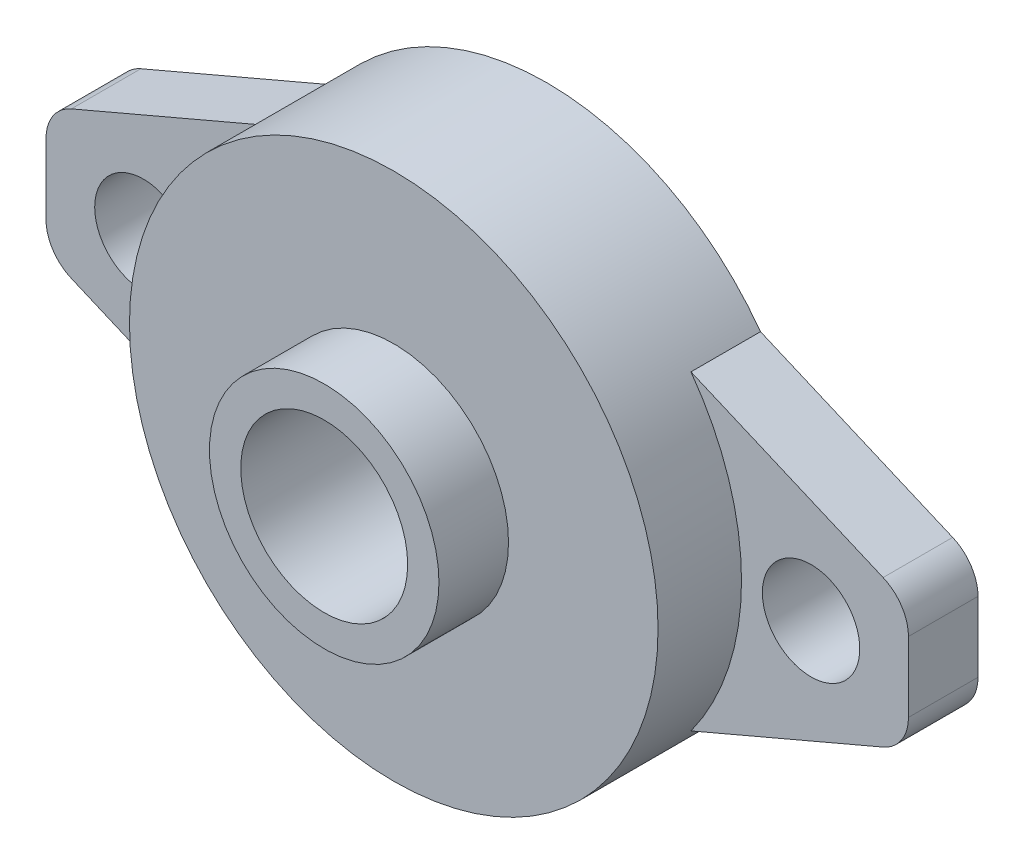
SolidWorks part; units mm, degrees
ref_plane "Front Plane" through (0, 0, 0) normal (0, 0, 1) x (1, 0, 0)
ref_plane "Top Plane" through (0, 0, 0) normal (0, 1, 0) x (1, 0, 0)
ref_plane "Right Plane" through (0, 0, 0) normal (1, 0, 0) x (0, 0, -1)
sketch "Sketch1" plane through (0, 0, 0) normal (0, 0, 1) x (1, 0, 0)
  circle A0 centre (0, 0) radius 19
  circle A1 centre (0, 0) radius 6
  dimension "D1" = 38
  dimension "D2" = 12
extrude "Boss-Extrude1" add sketch "Sketch1" along normal blind 11
sketch "Sketch2" plane through (0, 0, 11) normal (0, 0, 1) x (1, 0, 0)
  circle A0 centre (0, 0) radius 8.25
  circle A1 centre (0, 0) radius 6
  dimension "D1" = 16.5
extrude "Boss-Extrude2" add sketch "Sketch2" along normal blind 5
sketch "Sketch3" plane through (0, 0, 0) normal (0, 0, -1) x (-1, 0, 0)
  line L0 (31, 4.5) -> (31, -4.5)
  line L4 (15.3647, 11.1771) -> (31, 4.5)
  line L5 (15.3647, -11.1771) -> (31, -4.5)
  line L6 (-15.3647, -11.1771) -> (-31, -4.5)
  line L7 (-31, -4.5) -> (-31, 4.5)
  line L8 (-15.3647, 11.1771) -> (-31, 4.5)
  circle A0 centre (0, 0) radius 19 construction
  arc A1 (15.3647, -11.1771) -> (15.3647, 11.1771) centre (0, 0) ccw
  circle A2 centre (24, 0) radius 3.5
  circle A3 centre (-24, 0) radius 3.5
  arc A4 (-15.3647, 11.1771) -> (-15.3647, -11.1771) centre (0, 0) ccw
  point P18 (0, 0)
  dimension "D5" = 7
  dimension "D1" = 2
  dimension "D4" = 24
extrude "Boss-Extrude3" add sketch "Sketch3" against normal blind 5
fillet "Fillet1" radius 3 4 edges at (31, -4.5, 2.5) (31, 4.5, 2.5) (-31, -4.5, 2.5) (-31, 4.5, 2.5)
